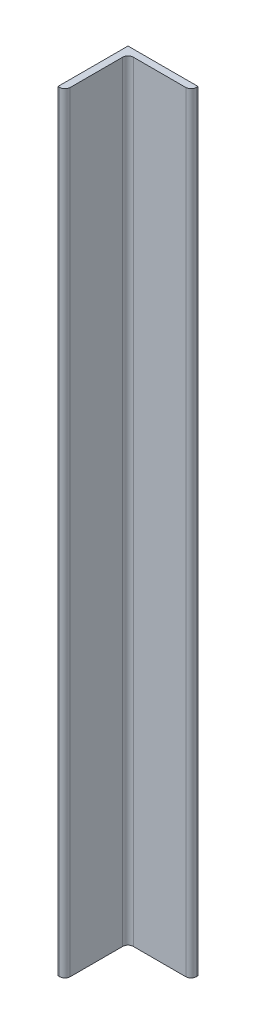
SolidWorks part; units mm, degrees
material "ASTM A36 Steel"
ref_plane "Front Plane" through (0, 0, 0) normal (0, 0, 1) x (1, 0, 0)
ref_plane "Top Plane" through (0, 0, 0) normal (0, 1, 0) x (1, 0, 0)
ref_plane "Right Plane" through (0, 0, 0) normal (1, 0, 0) x (0, 0, -1)
sketch "Sketch1" plane through (0, 0, 0) normal (0, 1, 0) x (1, 0, 0)
  line L0 (-27.4999, 29.2132) -> (-67.4999, 29.2132)
  line L1 (-67.4999, 29.2132) -> (-67.4999, -10.7868)
  line L2 (-67.4999, -10.7868) -> (-66.4999, -10.7868)
  line L3 (-63.4999, -7.7868) -> (-63.4999, 22.2132)
  line L4 (-60.4999, 25.2132) -> (-30.4999, 25.2132)
  line L5 (-27.4999, 28.2132) -> (-27.4999, 29.2132)
  arc A0 (-66.4999, -10.7868) -> (-63.4999, -7.7868) centre (-66.4999, -7.7868) ccw
  arc A1 (-63.4999, 22.2132) -> (-60.4999, 25.2132) centre (-60.4999, 22.2132) cw
  arc A2 (-30.4999, 25.2132) -> (-27.4999, 28.2132) centre (-30.4999, 28.2132) ccw
  point P8 (-63.4999, -10.7868)
  point P13 (-27.4999, 25.2132)
  dimension "D5" = 3
  dimension "D1" = 40
  dimension "D2" = 40
  dimension "D3" = 4
  dimension "D4" = 4
extrude "Boss-Extrude1" add sketch "Sketch1" along normal blind 440
